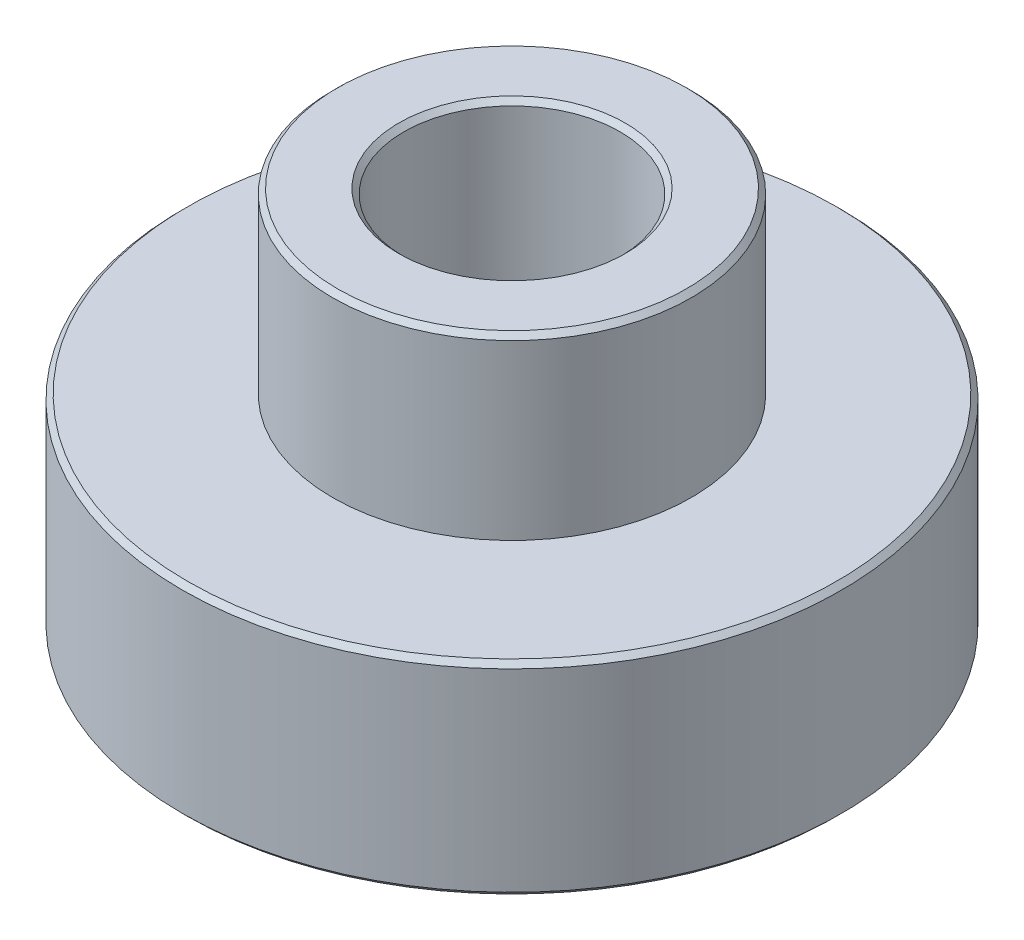
SolidWorks part; units mm, degrees
ref_plane "Front Plane" through (0, 0, 0) normal (0, 0, 1) x (1, 0, 0)
ref_plane "Top Plane" through (0, 0, 0) normal (0, 1, 0) x (1, 0, 0)
ref_plane "Right Plane" through (0, 0, 0) normal (1, 0, 0) x (0, 0, -1)
other "Configuration Table"
sketch "草图1" plane through (0, 0, 0) normal (0, 1, 0) x (1, 0, 0)
  circle A0 centre (0, 0) radius 12.95
  dimension "D1" = 25.9
extrude "凸台-拉伸1" add sketch "草图1" along normal blind 8
sketch "草图2" plane through (0, 8, 0) normal (0, 1, 0) x (1, 0, 0)
  circle A0 centre (0, 0) radius 7.05
  dimension "D1" = 14.1
extrude "凸台-拉伸2" add sketch "草图2" along normal blind 7
sketch "草图3" plane through (0, 0, 0) normal (0, -1, 0) x (1, 0, 0)
  circle A0 centre (0, 0) radius 4.25
  dimension "D1" = 8.5
extrude "切除-拉伸1" cut sketch "草图3" against normal through all
chamfer "倒角1" distance 0.2 angle 45 5 edges at (0, 0, -4.25) (0, 15, -4.25) (0, 15, 7.05) (0, 8, 12.95) (0, 0, 12.95)
